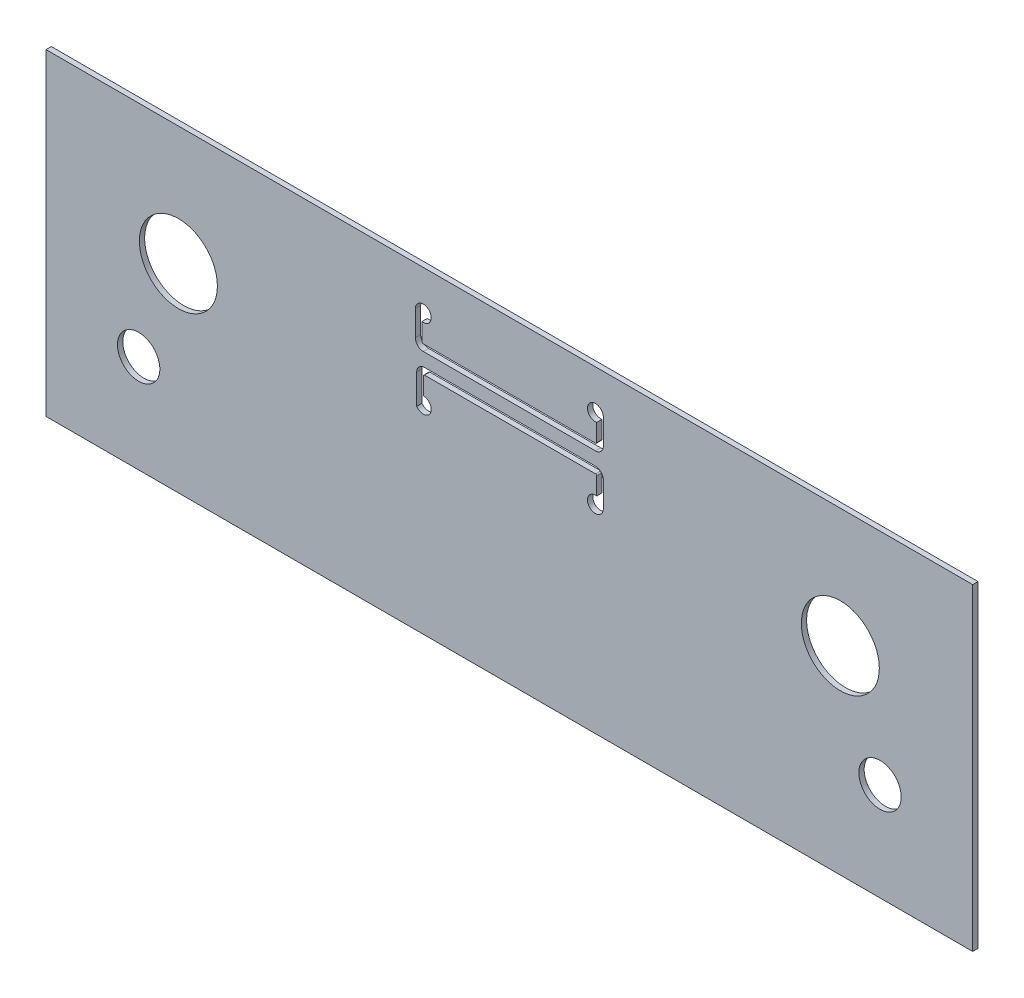
SolidWorks part; units mm, degrees
ref_plane "Front Plane" through (0, 0, 0) normal (0, 0, 1) x (1, 0, 0)
ref_plane "Top Plane" through (0, 0, 0) normal (0, 1, 0) x (1, 0, 0)
ref_plane "Right Plane" through (0, 0, 0) normal (1, 0, 0) x (0, 0, -1)
sketch "Sketch1" plane through (0, 0, 0) normal (0, 0, 1) x (1, 0, 0)
  line L0 (0, 0) -> (35, 0)
  line L1 (35, 0) -> (35, -12)
  line L2 (35, -12) -> (0, -12)
  line L3 (0, -12) -> (0, 0)
  line L5 (17.5, 4.0959) -> (17.5, -15.1104) construction
  line L6 (14.2, -1.7958) -> (14.2, -2.45)
  line L7 (14.25, -2.5) -> (20.75, -2.5)
  line L8 (20.8, -2.45) -> (20.8, -1.7958)
  line L9 (13.95, -1.5) -> (13.95, -2.45)
  line L10 (14.25, -2.75) -> (20.75, -2.75)
  line L11 (21.05, -2.45) -> (21.05, -1.5)
  line L12 (17.5, -2.5) -> (17.5, -2.75) construction
  line L13 (17.5, -2.5) -> (17.5, -2.75) construction
  line L14 (14.25, -4.2) -> (14.25, -3.55)
  line L15 (14.3, -3.5) -> (20.75, -3.5)
  line L16 (20.8, -3.55) -> (20.8, -4.2042)
  line L17 (21.05, -4.5) -> (21.05, -3.55)
  line L20 (20.75, -3.25) -> (14.3, -3.25)
  line L21 (14, -3.55) -> (14, -4.6658)
  circle A0 centre (3.5, -8.3) radius 0.8001
  circle A1 centre (5, -4.5) radius 1.4732
  arc A2 (14.2, -1.7958) -> (13.95, -1.5) centre (14.25, -1.5) ccw
  arc A3 (21.05, -1.5) -> (20.8, -1.7958) centre (20.75, -1.5) ccw
  arc A4 (20.8, -4.2042) -> (21.05, -4.5) centre (20.75, -4.5) ccw
  arc A5 (14, -4.6658) -> (14.25, -4.2) centre (14.25, -4.5) ccw
  circle A6 centre (30, -4.5) radius 1.4732
  circle A7 centre (31.5, -8.3) radius 0.8001
  arc A8 (14.2, -2.45) -> (14.25, -2.5) centre (14.25, -2.45) ccw
  arc A9 (20.75, -2.5) -> (20.8, -2.45) centre (20.75, -2.45) ccw
  arc A10 (13.95, -2.45) -> (14.25, -2.75) centre (14.25, -2.45) ccw
  arc A11 (20.75, -2.75) -> (21.05, -2.45) centre (20.75, -2.45) ccw
  arc A12 (14.25, -3.55) -> (14.3, -3.5) centre (14.3, -3.55) cw
  arc A13 (20.75, -3.5) -> (20.8, -3.55) centre (20.75, -3.55) cw
  arc A14 (21.05, -3.55) -> (20.75, -3.25) centre (20.75, -3.55) ccw
  arc A15 (14.3, -3.25) -> (14, -3.55) centre (14.3, -3.55) ccw
  point P14 (17.5, 0)
  point P47 (17.5, -2.625)
  dimension "D3" = 1.6002
  dimension "D5" = 6.5
  dimension "D13" = 3
  dimension "D18" = 8.3
  dimension "D34" = 2.9464
  dimension "D10" = 2.625
  dimension "D14" = 1.5
  dimension "D20" = 0.5
  dimension "D12" = 0.3
  dimension "D15" = 0.3
  dimension "D11" = 0.3
  dimension "D1" = 35
  dimension "D2" = 12
  dimension "D4" = 14.25
  dimension "D6" = 8.3
  dimension "D7" = 0.25
  dimension "D8" = 0.25
  dimension "D9" = 0.25
  dimension "D16" = 3.5
  dimension "D17" = 3.5
  dimension "D19" = 0.25
  dimension "D21" = 4.5
  dimension "D22" = 5
  dimension "D23" = 5
extrude "Boss-Extrude1" add sketch "Sketch1" along normal blind 0.2
